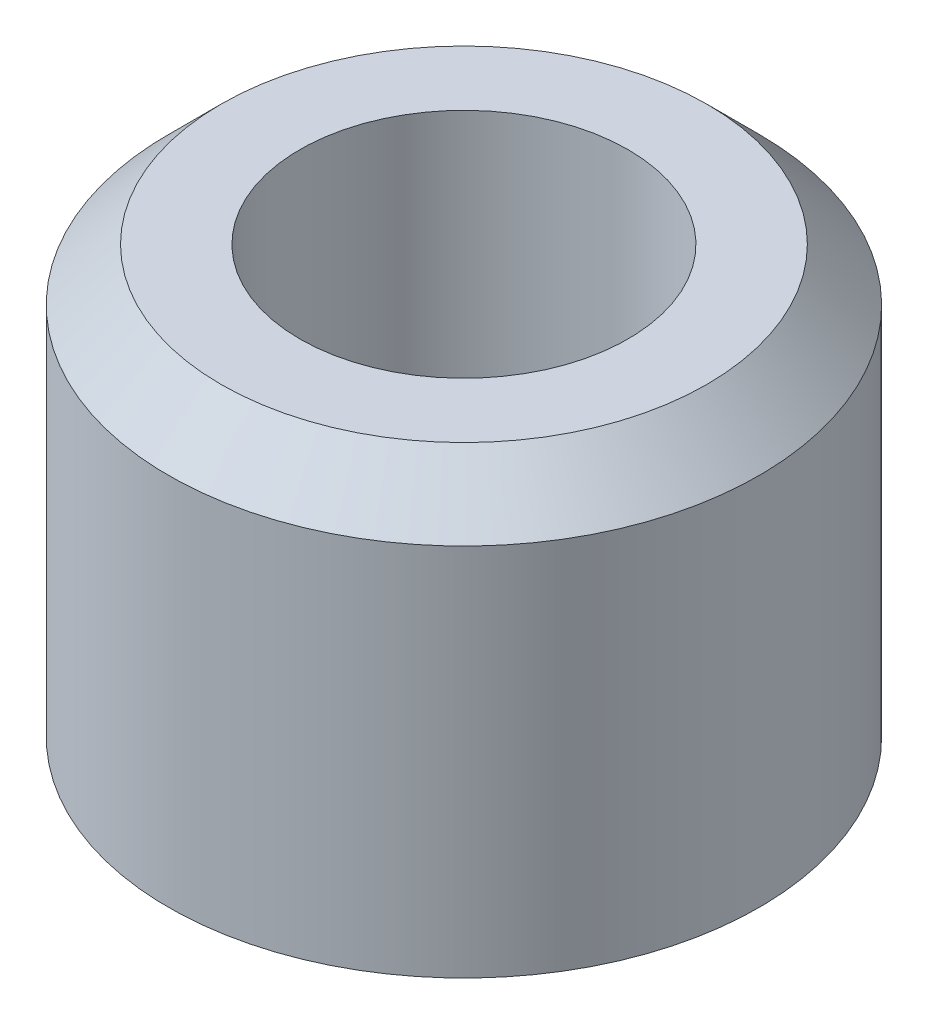
SolidWorks part; units mm, degrees
ref_plane "Спереди" through (0, 0, 0) normal (0, 0, 1) x (1, 0, 0)
ref_plane "Сверху" through (0, 0, 0) normal (0, 1, 0) x (1, 0, 0)
ref_plane "Справа" through (0, 0, 0) normal (1, 0, 0) x (0, 0, -1)
sketch "Эскиз1" plane through (0, 0, 0) normal (0, 1, 0) x (1, 0, 0)
  circle A0 centre (0, 0) radius 2.5
  circle A1 centre (0, 0) radius 4.5
  dimension "D1" = 5
  dimension "D2" = 9
extrude "Бобышка-Вытянуть1" add sketch "Эскиз1" along normal blind 6.5
chamfer "Фаска1" distance 0.8 angle 45 1 edges at (0, 6.5, 4.5)
